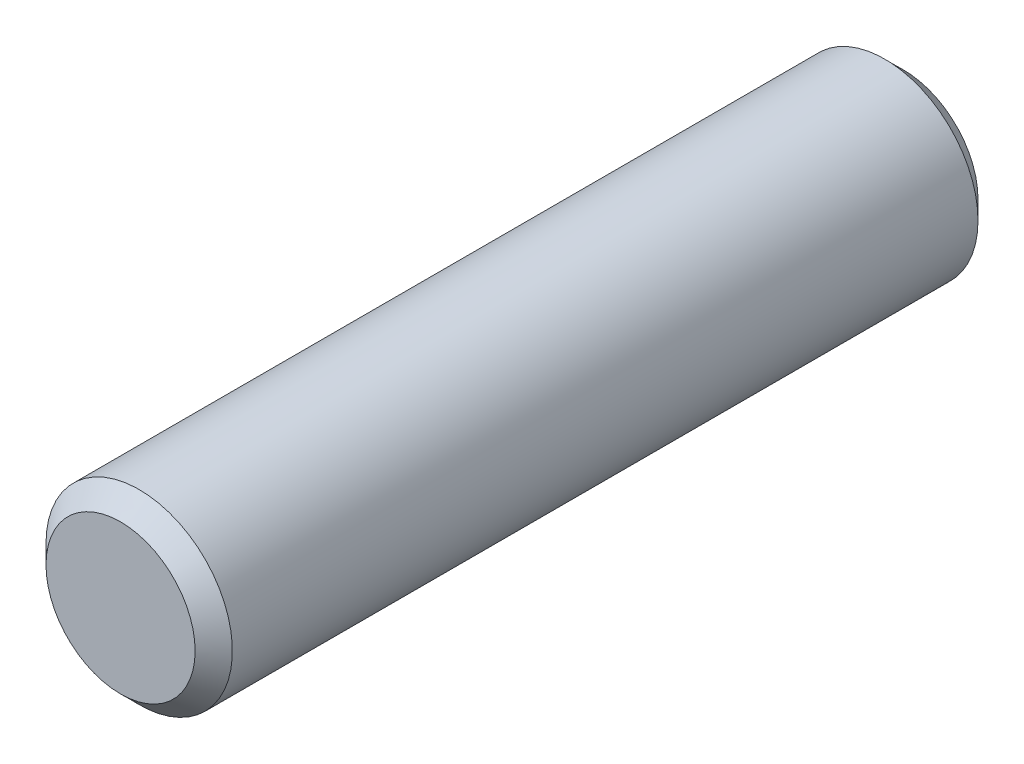
SolidWorks part; units mm, degrees
material "Alloy Steel"
ref_plane "Front Plane" through (0, 0, 0) normal (0, 0, 1) x (1, 0, 0)
ref_plane "Top Plane" through (0, 0, 0) normal (0, 1, 0) x (1, 0, 0)
ref_plane "Right Plane" through (0, 0, 0) normal (1, 0, 0) x (0, 0, -1)
sketch "Sketch1" plane through (0, 0, 0) normal (0, 0, 1) x (1, 0, 0)
  circle A0 centre (0, 0) radius 10
  dimension "D1" = 20
extrude "Boss-Extrude1" add sketch "Sketch1" along normal blind 84
chamfer "Chamfer1" distance 2 angle 45 2 edges at (10, 0, 0) (10, 0, 84)
